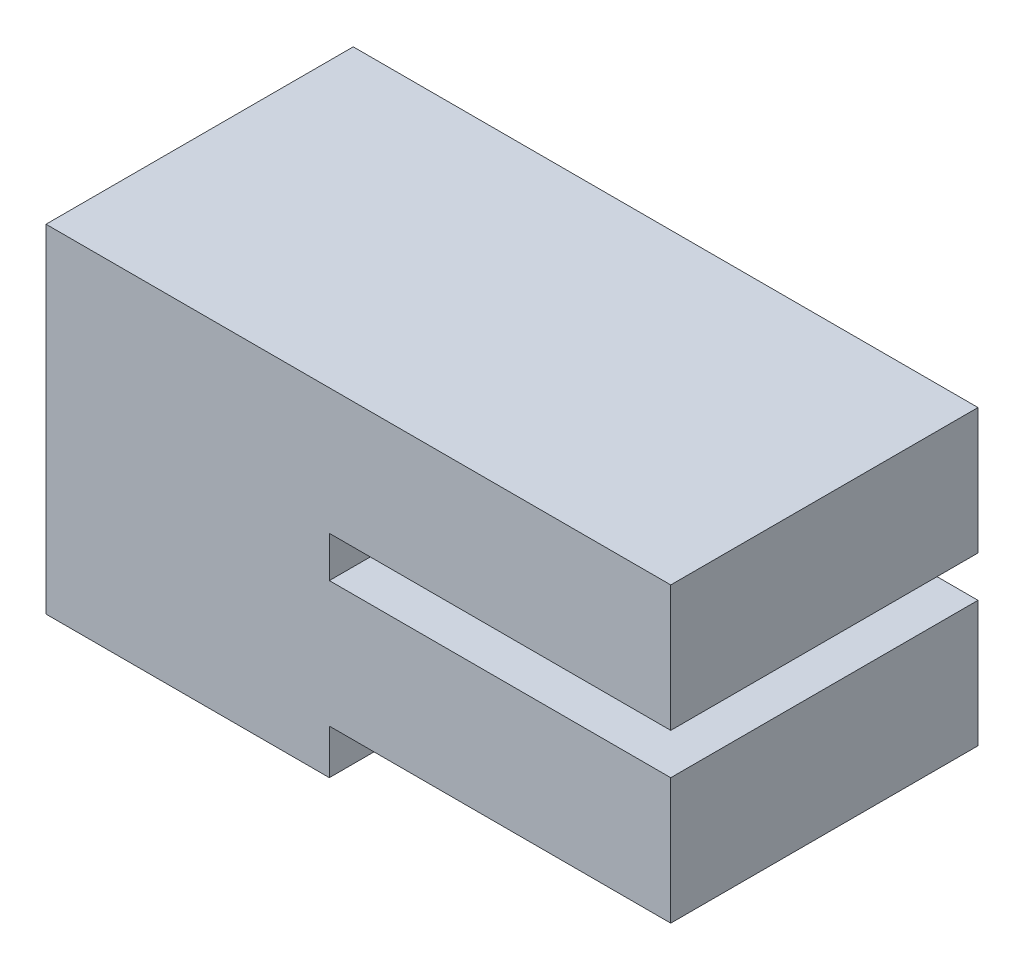
SolidWorks part; units mm, degrees
ref_plane "Front Plane" through (0, 0, 0) normal (0, 0, 1) x (1, 0, 0)
ref_plane "Top Plane" through (0, 0, 0) normal (0, 1, 0) x (1, 0, 0)
ref_plane "Right Plane" through (0, 0, 0) normal (1, 0, 0) x (0, 0, -1)
sketch "Sketch1" plane through (0, 0, 0) normal (0, 0, 1) x (1, 0, 0)
  line L1 (0, 0) -> (8.3, 0)
  line L2 (0, 0) -> (0, 9.8906)
  line L3 (0, 9.8906) -> (8.3, 9.8906)
  line L4 (8.3, 0) -> (8.3, 9.8906)
  dimension "D1" = 8.3
  dimension "D2" = 9.8906
extrude "Boss-Extrude1" add sketch "Sketch1" along normal blind 9
sketch "Sketch2" plane through (0, 0, 9) normal (0, 0, 1) x (1, 0, 0)
  line L0 (8.3, 0) -> (8.3, 9.8906) construction
  line L1 (8.3, 9.8906) -> (18.3, 9.8906)
  line L2 (8.3, 9.8906) -> (8.3, 6.2)
  line L3 (8.3, 6.2) -> (18.3, 6.2)
  line L4 (18.3, 9.8906) -> (18.3, 6.2)
  line L5 (8.3, 5) -> (18.3, 5)
  line L6 (8.3, 5) -> (8.3, 1.3094)
  line L7 (8.3, 1.3094) -> (18.3, 1.3094)
  line L8 (18.3, 5) -> (18.3, 1.3094)
  line L9 (8.3, 9.8906) -> (0, 9.8906) construction
  dimension "D1" = 1.2
  dimension "D2" = 4.8906
  dimension "D3" = 10
extrude "Boss-Extrude2" add sketch "Sketch2" against normal through all
